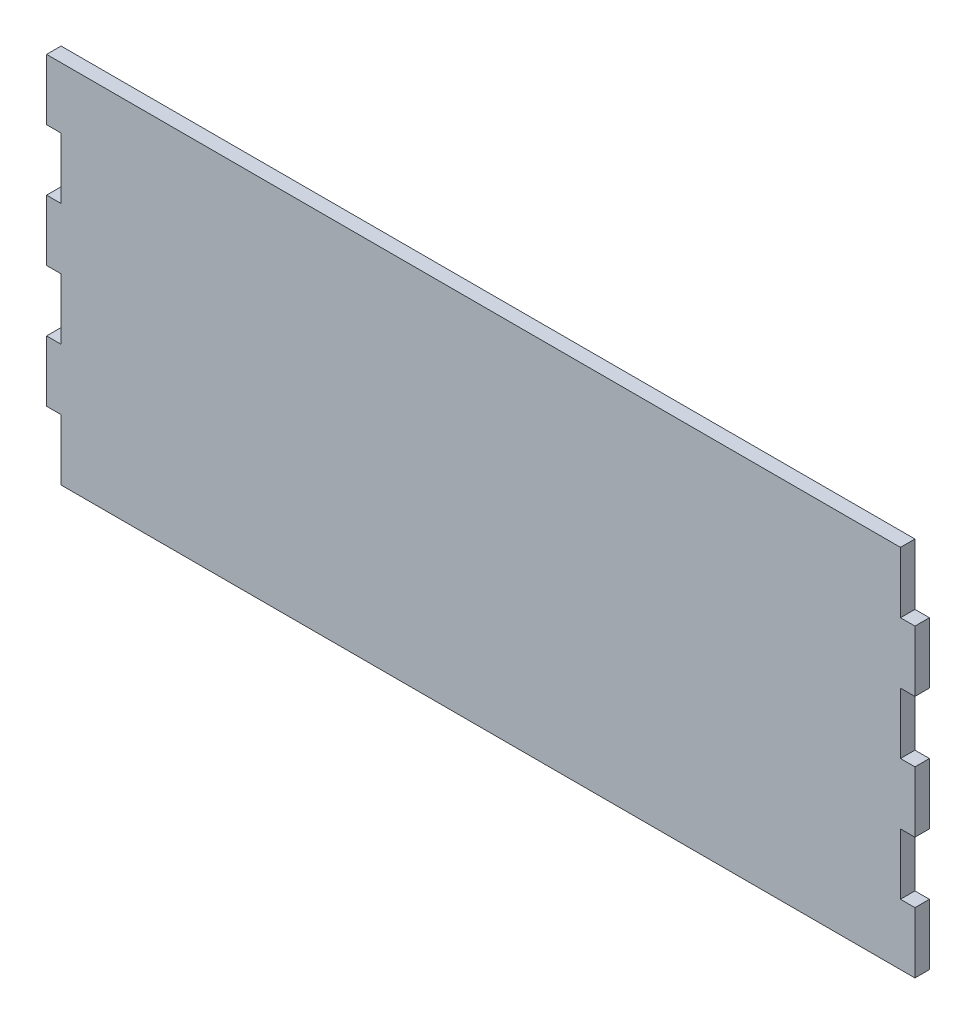
SolidWorks part; units mm, degrees
other "Marcação1"
sketch "Esboço2" plane through (-87, -37.905, 3) normal (-0.2137, -0.0419, 0.976) x (0.9769, -0.0031, 0.2137)
ref_plane "Plano frontal" through (0, 0, 0) normal (0, 0, 1) x (1, 0, 0)
ref_plane "Plano superior" through (0, 0, 0) normal (0, 1, 0) x (1, 0, 0)
ref_plane "Plano direito" through (0, 0, 0) normal (1, 0, 0) x (0, 0, -1)
sketch "Esboço1" plane through (0, 0, 0) normal (0, 0, 1) x (1, 0, 0)
  line L1 (87, -37.905) -> (-87, -37.905)
  line L2 (87, -37.905) -> (87, 37.905)
  line L3 (87, 37.905) -> (-87, 37.905)
  line L4 (-87, -37.905) -> (-87, 37.905)
  line L5 (87, -37.905) -> (-87, 37.905) construction
  line L6 (87, 37.905) -> (-87, -37.905) construction
  point P0 (0, 0)
  dimension "D1" = 174
  dimension "D2" = 75.81
extrude "Ressalto-extrusão1" add sketch "Esboço1" along normal blind 3
sketch "Esboço3" plane through (0, 0, 3) normal (0, 0, 1) x (1, 0, 0)
  line L0 (-87, 12.635) -> (-87, 0)
  line L1 (-87, 37.905) -> (-90, 37.905)
  line L2 (-87, 37.905) -> (-87, 25.27)
  line L3 (-87, 25.27) -> (-90, 25.27)
  line L4 (-90, 37.905) -> (-90, 25.27)
  line L5 (-87, 12.635) -> (-90, 12.635)
  line L6 (-90, 12.635) -> (-90, 0)
  line L7 (-87, 0) -> (-90, 0)
  line L8 (-87, -12.635) -> (-87, -25.27)
  line L9 (-87, -12.635) -> (-90, -12.635)
  line L10 (-90, -12.635) -> (-90, -25.27)
  line L11 (-87, -25.27) -> (-90, -25.27)
  dimension "D1" = 12.635
  dimension "D2" = 3
  dimension "D4" = 12.635
  dimension "D3" = 3
extrude "Ressalto-extrusão2" add sketch "Esboço3" against normal blind 3
sketch "Esboço4" plane through (0, 0, 3) normal (0, 0, 1) x (1, 0, 0)
  line L0 (87, -37.905) -> (87, 37.905) construction
  line L1 (87, 25.27) -> (90, 25.27)
  line L2 (87, 25.27) -> (87, 12.635)
  line L3 (87, 12.635) -> (90, 12.635)
  line L4 (90, 25.27) -> (90, 12.635)
  line L5 (87, 37.905) -> (-90, 37.905) construction
  line L6 (87, 0) -> (87, -12.635)
  line L7 (87, 0) -> (90, 0)
  line L8 (90, 0) -> (90, -12.635)
  line L9 (87, -12.635) -> (90, -12.635)
  line L10 (87, -25.27) -> (87, -37.905)
  line L11 (87, -25.27) -> (90, -25.27)
  line L12 (90, -25.27) -> (90, -37.905)
  line L13 (87, -37.905) -> (90, -37.905)
  dimension "D1" = 3
  dimension "D2" = 12.635
  dimension "D3" = 12.635
  dimension "D5" = 12.635
  dimension "D4" = 3
extrude "Ressalto-extrusão3" add sketch "Esboço4" against normal blind 3
